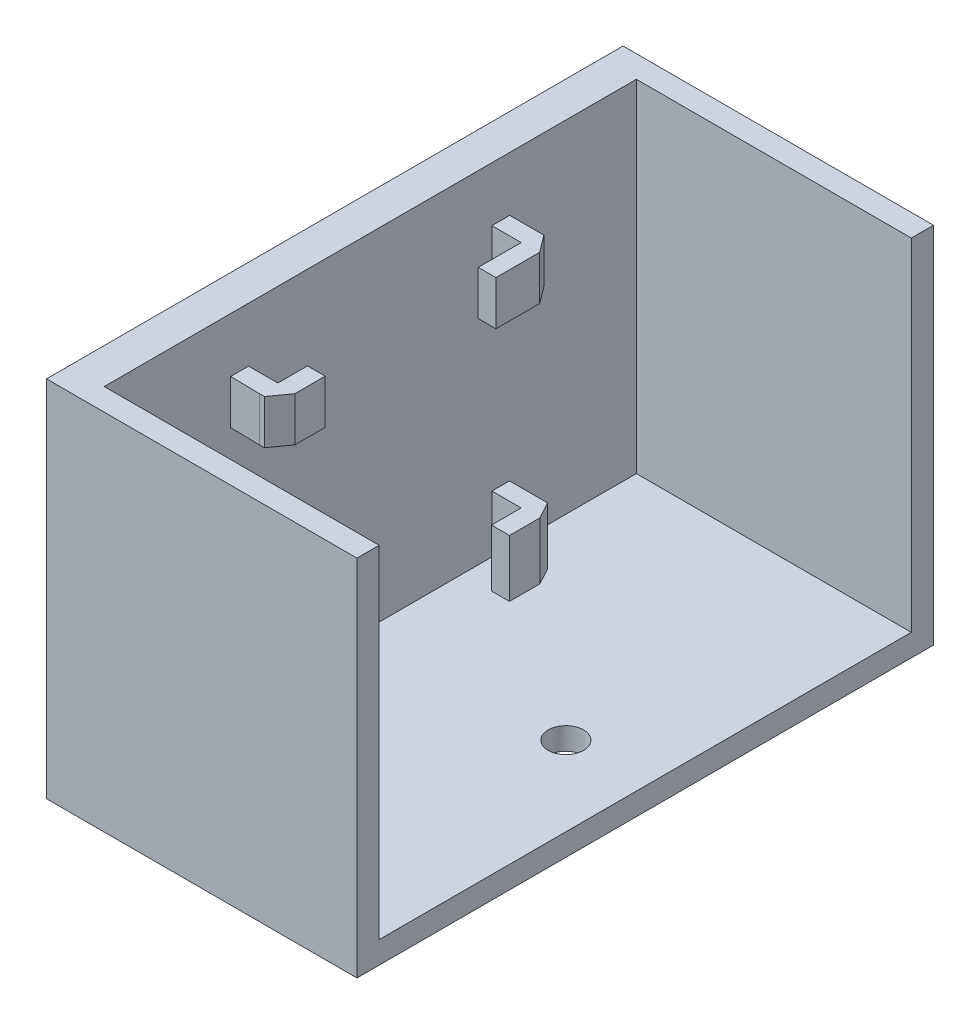
SolidWorks part; units mm, degrees
ref_plane "Front Plane" through (0, 0, 0) normal (0, 0, 1) x (1, 0, 0)
ref_plane "Top Plane" through (0, 0, 0) normal (0, 1, 0) x (1, 0, 0)
ref_plane "Right Plane" through (0, 0, 0) normal (1, 0, 0) x (0, 0, -1)
sketch "Sketch1" plane through (0, 0, 0) normal (0, 1, 0) x (1, 0, 0)
  line L1 (-17.5, -32.5) -> (17.5, -32.5)
  line L2 (-17.5, -32.5) -> (-17.5, 32.5)
  line L3 (-17.5, 32.5) -> (17.5, 32.5)
  line L4 (17.5, -32.5) -> (17.5, 32.5)
  line L5 (0, 32.5) -> (0, -32.5) construction
  line L6 (-17.5, 0) -> (17.5, 0) construction
  point P0 (0, 0)
  dimension "D1" = 65
  dimension "D2" = 35
extrude "Boss-Extrude1" add sketch "Sketch1" along normal blind 2.5
sketch "Sketch2" plane through (0, 2.5, 0) normal (0, 1, 0) x (1, 0, 0)
  line L0 (-17.5, -32.5) -> (17.5, -32.5) construction
  line L1 (-17.5, 32.5) -> (-13.5, 32.5)
  line L2 (-17.5, 32.5) -> (-17.5, -32.5)
  line L3 (-17.5, -32.5) -> (-13.5, -32.5)
  line L4 (-13.5, 32.5) -> (-13.5, -32.5)
  dimension "D1" = 4
extrude "Boss-Extrude2" add sketch "Sketch2" along normal blind 38.5
sketch "Sketch3" plane through (0, 2.5, 0) normal (0, 1, 0) x (1, 0, 0)
  line L0 (-13.5, -32.5) -> (-13.5, 32.5) construction
  line L1 (17.5, 32.5) -> (-13.5, 32.5)
  line L2 (17.5, 32.5) -> (17.5, 30)
  line L3 (17.5, 30) -> (-13.5, 30)
  line L4 (-13.5, 32.5) -> (-13.5, 30)
  line L5 (-1.375, 0) -> (1.375, 0) construction
  line L6 (17.5, -30) -> (-13.5, -30)
  line L7 (-13.5, -32.5) -> (-13.5, -30)
  line L8 (17.5, -32.5) -> (-13.5, -32.5)
  line L9 (17.5, -32.5) -> (17.5, -30)
extrude "Boss-Extrude4" add sketch "Sketch3" along normal blind 38.5
sketch "Sketch6" plane through (-13.5, 0, 0) normal (1, 0, 0) x (0, 0, -1)
  line L0 (0, 41) -> (0, 2.5)
  line L1 (-30, 41) -> (30, 41) construction
  line L2 (-30, 2.5) -> (30, 2.5) construction
sketch "Sketch7" plane through (0, 2.5, 0) normal (0, 1, 0) x (1, 0, 0)
  line L7 (-13.5, -30) -> (-13.5, 30) construction
  line L11 (-13.5, 13.7173) -> (-13.5, 15.6968)
  line L22 (-8.1733, 13.7967) -> (-9.2037, 15.6968)
  line L23 (-9.2037, 15.6968) -> (-13.5, 15.6968)
  line L24 (-8.1733, 13.7967) -> (-8.1733, 11.874)
  line L25 (-19.25, 0) -> (19.25, 0) construction
  line L30 (-13.5, -13.7173) -> (-13.5, -15.6968)
  line L34 (-8.1733, 11.874) -> (-8.1733, 10.3672)
  line L35 (-8.1733, 10.3672) -> (-10.2, 10.3672)
  line L40 (-13.5, -13.7173) -> (-10.2, -13.7173)
  line L41 (-10.2, -13.7173) -> (-10.2, -10.374)
  line L42 (-10.2, -10.374) -> (-8.2038, -10.374)
  line L43 (-8.2038, -10.374) -> (-8.2038, -13.7173)
  line L44 (-8.2038, -13.7173) -> (-9.2037, -15.6968)
  line L46 (-10.2, 13.7173) -> (-13.5, 13.7173)
  line L47 (-10.2, 10.3672) -> (-10.2, 13.7173)
  line L48 (-9.2037, -15.6968) -> (-13.5, -15.6968)
  point P2 (-9.2037, -15.6968)
sketch "Sketch11" plane through (-13.5, 0, 0) normal (1, 0, 0) x (0, 0, -1)
  line L0 (-12.9244, 36.8) -> (-15.4807, 36.8)
ref_plane "Plane1" through (0, 41, 0) normal (0, 1, 0) x (1, 0, 0)
sketch "Sketch12" plane through (0, 41, 0) normal (0, 1, 0) x (1, 0, 0)
  line L7 (-19.25, 0) -> (19.25, 0) construction
  line L15 (-8.2038, -13.7967) -> (-9.645, -15.7928)
  line L22 (-13.5, 13.7173) -> (-10.2, 13.7173)
  line L23 (-10.2, 13.7173) -> (-10.2, 8.874)
  line L24 (-10.2, 8.874) -> (-8.2038, 8.874)
  line L25 (-8.2038, 8.874) -> (-8.2038, 13.7967)
  line L26 (-8.2038, 13.7967) -> (-9.645, 15.7215)
  line L27 (-9.645, 15.7215) -> (-13.5, 15.7215)
  line L28 (-13.5, 15.7215) -> (-13.5, 13.7173)
  line L29 (-8.2038, -10.374) -> (-8.2038, -13.7967)
  line L31 (-10.2, -15.7928) -> (-13.5, -15.7402)
  line L33 (-10.2, -10.374) -> (-8.2038, -10.374)
  line L34 (-9.645, -15.7928) -> (-10.2, -15.7928)
  line L35 (-13.5, -15.7402) -> (-13.5, -13.7173)
  line L36 (-10.2, -10.374) -> (-10.2, -13.7173)
  line L37 (-10.2, -13.7173) -> (-13.5, -13.7173)
sketch "Sketch13" plane through (-13.5, 0, 0) normal (1, 0, 0) x (0, 0, -1)
  line L0 (-15.7193, 34.85) -> (-19.0508, 34.85)
  line L1 (-19.0508, 34.85) -> (-19.0508, 41)
  line L3 (-15.7402, 41) -> (21.5659, 41)
  line L5 (-15.7193, 34.85) -> (21.5659, 34.85)
  line L7 (-30, 41) -> (30, 41) construction
  line L8 (-19.0508, 41) -> (-15.7402, 41)
  line L9 (21.5659, 41) -> (24.3324, 41)
  line L10 (24.3324, 41) -> (24.3324, 34.85)
  line L11 (24.3324, 34.85) -> (21.5659, 34.85)
extrude "Boss-Extrude6" add sketch "Sketch12" against normal blind 11.15
sketch "Sketch15" plane through (0, 2.5, 0) normal (0, 1, 0) x (1, 0, 0)
  line L0 (-17.4499, 0) -> (8.5501, 0)
  circle A0 centre (8.5501, 0) radius 2
extrude "Cut-Extrude3" cut sketch "Sketch15" against normal blind 5
extrude "Cut-Extrude6" cut sketch "Sketch13" along normal blind 7 contours L3 L9 L10 L11 L5 L0 L1 L8
extrude "Boss-Extrude7" add sketch "Sketch7" along normal blind 6.44
